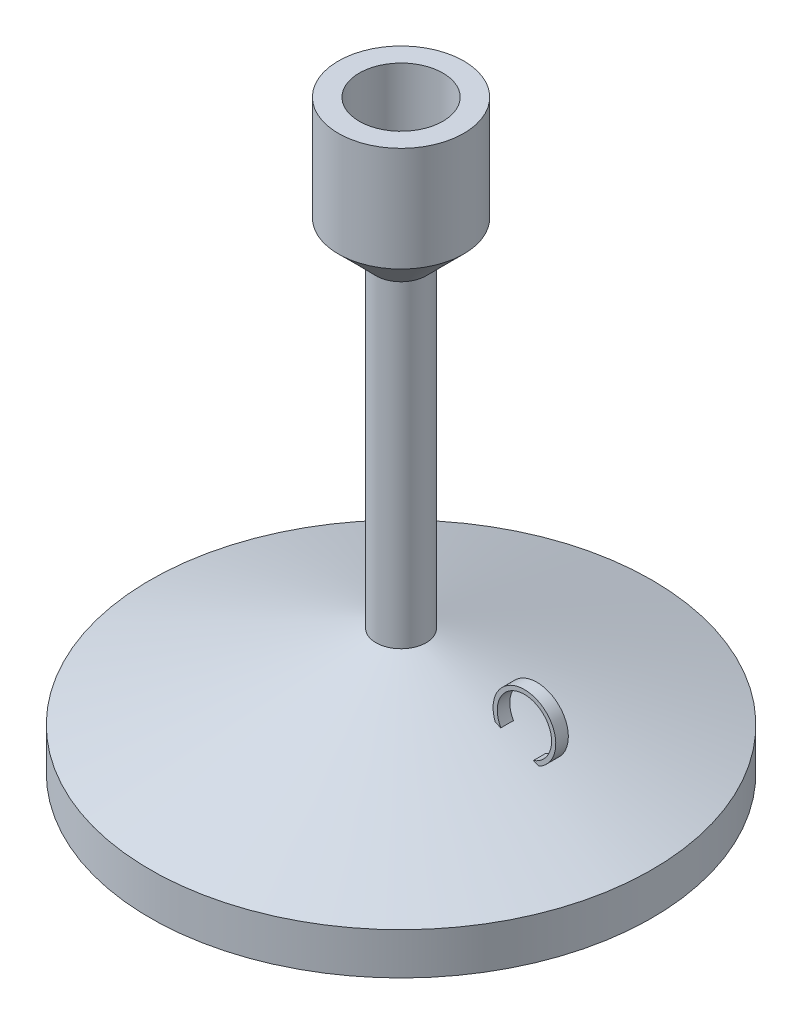
SolidWorks part; units mm, degrees
ref_plane "Front Plane" through (0, 0, 0) normal (0, 0, 1) x (1, 0, 0)
ref_plane "Top Plane" through (0, 0, 0) normal (0, 1, 0) x (1, 0, 0)
ref_plane "Right Plane" through (0, 0, 0) normal (1, 0, 0) x (0, 0, -1)
sketch "Sketch1" plane through (0, 0, 0) normal (0, 0, 1) x (1, 0, 0)
  line L0 (0, 0) -> (0, 140) construction
  line L1 (0, 140) -> (-15, 140)
  line L2 (-15, 140) -> (-15, 115)
  line L3 (-15, 115) -> (-6, 106)
  line L4 (-6, 106) -> (-6, 30)
  line L5 (-6, 30) -> (-60, 10)
  line L6 (-60, 10) -> (-60, 0)
  line L7 (-60, 0) -> (0, 0)
  line L8 (0, 0) -> (0, 140)
  dimension "D1" = 140
  dimension "D2" = 12
  dimension "D3" = 135
  dimension "D4" = 25
  dimension "D5" = 10
  dimension "D6" = 120
  dimension "D7" = 30
  dimension "D8" = 30
revolve "Revolve1" add sketch "Sketch1" angle 360 about L0
sketch "Sketch2" plane through (0, 140, 0) normal (0, 1, 0) x (1, 0, 0)
  circle A0 centre (0, 0) radius 10
  circle A1 centre (0, 0) radius 15 construction
  dimension "D1" = 20
  dimension "D2" = 0
extrude "Cut-Extrude2" cut sketch "Sketch2" against normal blind 20
sketch "Sketch3" plane through (0, 0, 0) normal (0, 0, 1) x (1, 0, 0)
  line L0 (60, 10) -> (6, 30) construction
  circle A0 centre (31, 26.0727) radius 6.5
  circle A1 centre (31, 26.0727) radius 7.5
  dimension "D1" = 5
  dimension "D2" = 13
  dimension "D3" = 15
  dimension "D4" = 25
extrude "Boss-Extrude2" add sketch "Sketch3" along normal mid plane 3 contours A1
